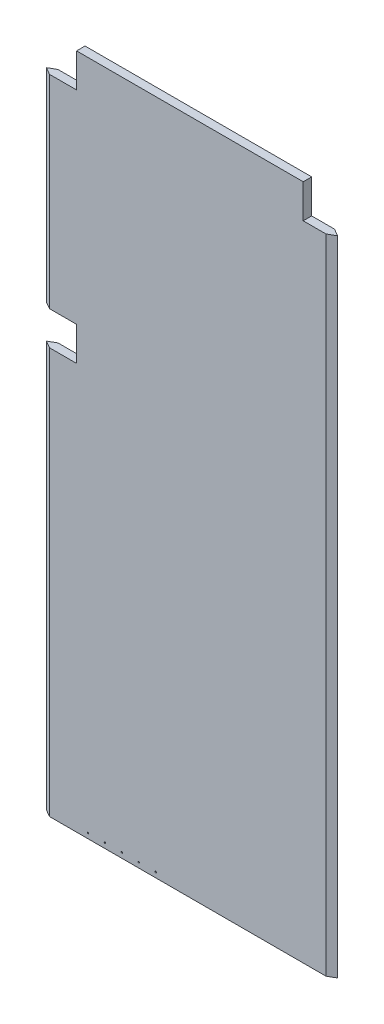
SolidWorks part; units mm, degrees
ref_plane "前视基准面" through (0, 0, 0) normal (0, 0, 1) x (1, 0, 0)
ref_plane "上视基准面" through (0, 0, 0) normal (0, 1, 0) x (1, 0, 0)
ref_plane "右视基准面" through (0, 0, 0) normal (1, 0, 0) x (0, 0, -1)
sketch "草图1" plane through (0, 0, 0) normal (0, 1, 0) x (1, 0, 0)
  line L0 (294.9442, 12.5) -> (294.9442, -12.5) construction
  line L1 (-375, 12.5) -> (375, 12.5)
  line L2 (-375, 12.5) -> (-375, -12.5)
  line L3 (-375, -12.5) -> (375, -12.5)
  line L4 (375, 12.5) -> (375, -12.5)
  line L5 (-375, 12.5) -> (375, -12.5) construction
  line L6 (-375, -12.5) -> (375, 12.5) construction
  line L7 (294.9442, 12.5) -> (294.9442, -12.5)
  point P0 (0, 0)
  dimension "D1" = 25
  dimension "D2" = 750
extrude "凸台-拉伸1" add sketch "草图1" along normal blind 2000 contours L7 L1 L2 L3
sketch "草图2" plane through (0, 0, 0) normal (0, -1, 0) x (1, 0, 0)
  line L0 (294.9442, 12.5) -> (362.4112, 12.5)
  line L1 (-375, 12.5) -> (294.9442, 12.5) construction
  line L2 (294.9442, -12.5) -> (294.9442, 12.5) construction
  line L3 (384.0619, 0) -> (359.0771, 14.425) construction
  line L4 (362.4112, 12.5) -> (384.0619, 0)
  line L5 (384.0619, 0) -> (362.4112, -12.5)
  line L6 (362.4112, -12.5) -> (294.9442, -12.5)
  line L7 (294.9442, -12.5) -> (294.9442, 12.5)
extrude "凸台-拉伸2" add sketch "草图2" against normal up to surface (1900 mm away)
sketch "草图3" plane through (0, 0, 0) normal (0, -1, 0) x (1, 0, 0)
  line L0 (-375, 12.5) -> (-455.0058, 12.5)
  line L2 (-455.0058, 12.5) -> (-476.6564, 0)
  line L3 (-476.6564, 0) -> (-455.0058, -12.5)
  line L5 (-455.0058, -12.5) -> (-375, -12.5)
  line L6 (-375, -12.5) -> (-375, 12.5)
  line L7 (-476.6564, 0) -> (-451.7173, 14.3986) construction
  line L8 (-476.6564, 0) -> (-451.7173, -14.3986) construction
extrude "凸台-拉伸3" add sketch "草图3" against normal up to surface (1900 mm away)
sketch "草图5" plane through (0, 0, -12.5) normal (0, 0, -1) x (-1, 0, 0)
  line L0 (375, 1300) -> (325.0941, 1300) construction
  line L1 (375, 1200) -> (325.0941, 1200) construction
  line L2 (375, 1300) -> (325.0941, 1300)
  line L3 (375, 1200) -> (325.0941, 1200)
  line L4 (375, 1200) -> (375, 1300)
  line L5 (375, 1200) -> (476.6564, 1200)
  line L6 (476.6564, 1900) -> (476.6564, 0) construction
  line L7 (476.6564, 1200) -> (476.6564, 1300)
  line L8 (476.6564, 1300) -> (375, 1300)
  line M2 (455.0058, 0) -> (455.0058, 1900)
extrude "切除-拉伸1" cut sketch "草图5" against normal up to next contours L7 L8 L5 M2 | L8 L4 L5 M2
sketch "草图8" plane through (0, 0, 12.5) normal (0, 0, 1) x (1, 0, 0)
  line L0 (-455.0058, 0) -> (362.4112, 0) construction
  line L1 (-455.0058, 1200) -> (-455.0058, 0) construction
  circle A0 centre (-341.2258, 15) radius 2.5
  point P6 (-379.1191, 16.8873)
  point P7 (-380.5716, 13.9396)
  dimension "D1" = 5
  dimension "D2" = 15
  dimension "D3" = 113.78
hole_wizard "M5 螺纹孔2" positions "3D草图2" profile "草图9" tap size "M5" standard "GB" end condition up to next
sketch3d "3D草图2"
  point P0 (-341.2258, 15, 12.5)
sketch "草图9" plane through (-341.2258, 15, 12.5) normal (1, 0, 0) x (0, -1, 0)
  line L0 (0, 0) -> (0, 25)
  line L1 (0, 25) -> (2.1, 25)
  line L2 (2.1, 25) -> (2.1, 0)
  line L5 (2.1, 0) -> (0, 0)
  line L11 (0, -6.35) -> (0, 107.95) construction
  dimension "通孔螺纹孔钻头直径" = 4.2
  dimension "通孔螺纹孔钻头深度" = 25
pattern_linear "阵列(线性)2" count 5 spacing 50 along (1, 0, 0) of "M5 螺纹孔2"
